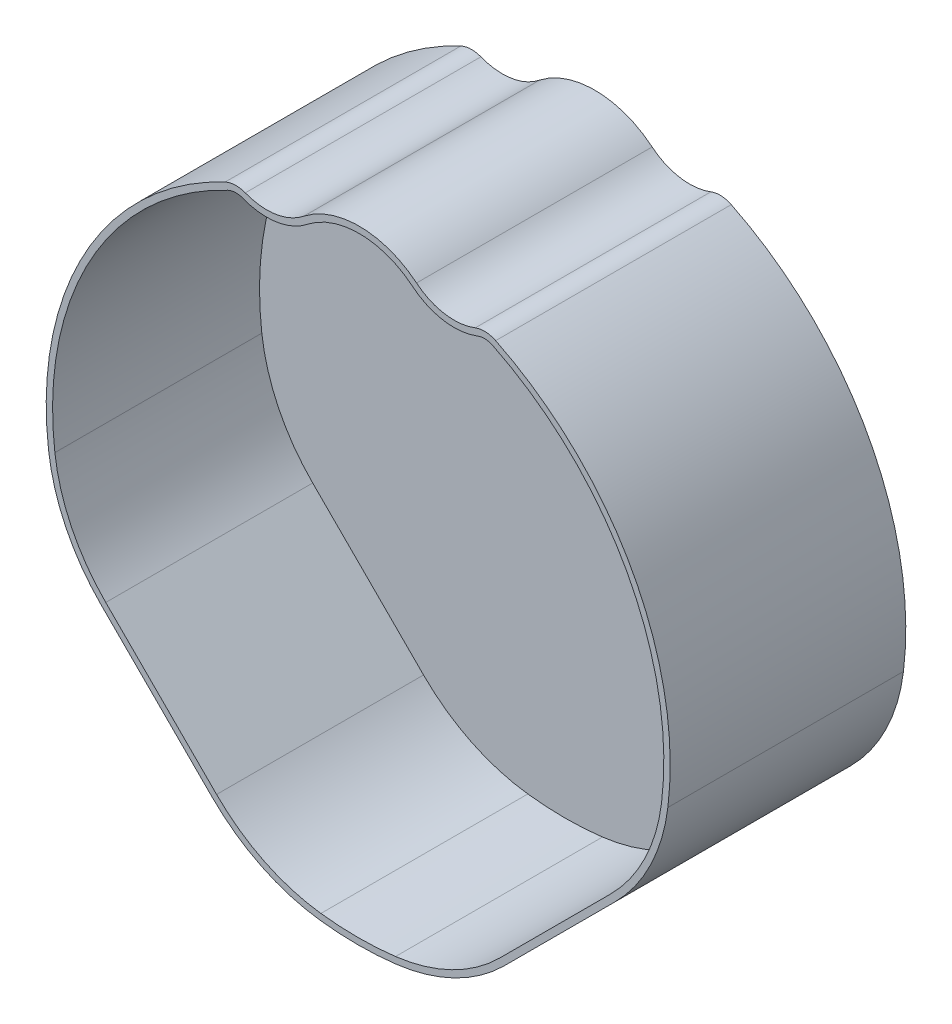
SolidWorks part; units mm, degrees
ref_plane "Front Plane" through (0, 0, 0) normal (0, 0, 1) x (1, 0, 0)
ref_plane "Top Plane" through (0, 0, 0) normal (0, 1, 0) x (1, 0, 0)
ref_plane "Right Plane" through (0, 0, 0) normal (1, 0, 0) x (0, 0, -1)
sketch "Sketch1" plane through (0, 0, 0) normal (0, 0, 1) x (1, 0, 0)
  line L0 (40.3565, -22.9474) -> (22.9474, -40.3565)
  line L1 (-22.9474, -40.3565) -> (-40.3565, -22.9474)
  arc A0 (-17.7314, 44.4305) -> (-8.4882, 45.8998) centre (-14.3636, 53.0521) ccw
  arc A1 (-8.4882, 45.8998) -> (9.1639, 45.6208) centre (0.1631, 34.7024) cw
  arc A2 (9.1639, 45.6208) -> (18.3859, 44.1282) centre (15.0517, 52.763) ccw
  arc A3 (18.3859, 44.1282) -> (21.5891, 43.9876) centre (19.8268, 40.3968) cw
  arc A4 (21.5891, 43.9876) -> (48.6336, -5.9813) centre (0, 0) cw
  arc A5 (48.6336, -5.9813) -> (40.3565, -22.9474) centre (19.8504, -2.4413) cw
  arc A6 (22.9474, -40.3565) -> (5.9813, -48.6336) centre (2.4413, -19.8504) cw
  arc A7 (5.9813, -48.6336) -> (-5.9813, -48.6336) centre (0, 0) cw
  arc A8 (-5.9813, -48.6336) -> (-22.9474, -40.3565) centre (-2.4413, -19.8504) cw
  arc A9 (-40.3565, -22.9474) -> (-48.6336, -5.9813) centre (-19.8504, -2.4413) cw
  arc A10 (-48.6336, -5.9813) -> (-20.8923, 44.3228) centre (0, 0) cw
  arc A11 (-20.8923, 44.3228) -> (-17.7314, 44.4305) centre (-19.1868, 40.7046) cw
  dimension "D1" = 9.2561
  dimension "D2" = 14.1501
  dimension "D3" = 4
  dimension "D4" = 49
  dimension "D5" = 29
  dimension "D6" = 0.1631
  dimension "D7" = 2.4413
  dimension "D8" = 9.1639
  dimension "D9" = 18.3859
  dimension "D10" = 8.4882
  dimension "D11" = 14.3636
extrude "Boss-Extrude1" add sketch "Sketch1" along normal blind 37
sketch "Sketch3" plane through (0, 0, 37) normal (0, 0, 1) x (1, 0, 0)
  line L4 (-39.6494, -22.2403) -> (-22.2403, -39.6494)
  line L5 (22.2403, -39.6494) -> (39.6494, -22.2403)
  line L6 (-39.6494, -22.2403) -> (-22.2403, -39.6494)
  line L7 (22.2403, -39.6494) -> (39.6494, -22.2403)
  arc A24 (-18.0953, 43.499) -> (-20.4659, 43.4183) centre (-19.1868, 40.7046) ccw
  arc A25 (-20.4659, 43.4183) -> (-47.6411, -5.8592) centre (0, 0) ccw
  arc A26 (-47.6411, -5.8592) -> (-39.6494, -22.2403) centre (-19.8504, -2.4413) ccw
  arc A27 (-22.2403, -39.6494) -> (-5.8592, -47.6411) centre (-2.4413, -19.8504) ccw
  arc A28 (-5.8592, -47.6411) -> (5.8592, -47.6411) centre (0, 0) ccw
  arc A29 (5.8592, -47.6411) -> (22.2403, -39.6494) centre (2.4413, -19.8504) ccw
  arc A30 (39.6494, -22.2403) -> (47.6411, -5.8592) centre (19.8504, -2.4413) ccw
  arc A31 (47.6411, -5.8592) -> (21.1485, 43.0899) centre (0, 0) ccw
  arc A32 (21.1485, 43.0899) -> (18.7461, 43.1954) centre (19.8268, 40.3968) ccw
  arc A33 (8.5278, 44.8492) -> (18.7461, 43.1954) centre (15.0517, 52.763) ccw
  arc A34 (8.5278, 44.8492) -> (-7.8655, 45.1172) centre (0.1631, 34.7024) ccw
  arc A35 (-18.0953, 43.499) -> (-7.8655, 45.1172) centre (-14.3636, 53.0521) ccw
  arc A36 (-18.0953, 43.499) -> (-20.4659, 43.4183) centre (-19.1868, 40.7046) ccw
  arc A37 (-20.4659, 43.4183) -> (-47.6411, -5.8592) centre (0, 0) ccw
  arc A38 (-47.6411, -5.8592) -> (-39.6494, -22.2403) centre (-19.8504, -2.4413) ccw
  arc A39 (-22.2403, -39.6494) -> (-5.8592, -47.6411) centre (-2.4413, -19.8504) ccw
  arc A40 (-5.8592, -47.6411) -> (5.8592, -47.6411) centre (0, 0) ccw
  arc A41 (5.8592, -47.6411) -> (22.2403, -39.6494) centre (2.4413, -19.8504) ccw
  arc A42 (39.6494, -22.2403) -> (47.6411, -5.8592) centre (19.8504, -2.4413) ccw
  arc A43 (47.6411, -5.8592) -> (21.1485, 43.0899) centre (0, 0) ccw
  arc A44 (21.1485, 43.0899) -> (18.7461, 43.1954) centre (19.8268, 40.3968) ccw
  arc A45 (8.5278, 44.8492) -> (18.7461, 43.1954) centre (15.0517, 52.763) ccw
  arc A46 (8.5278, 44.8492) -> (-7.8655, 45.1172) centre (0.1631, 34.7024) ccw
  arc A47 (-18.0953, 43.499) -> (-7.8655, 45.1172) centre (-14.3636, 53.0521) ccw
  dimension "D1" = 1
extrude "Cut-Extrude1" cut sketch "Sketch3" against normal blind 32.5
